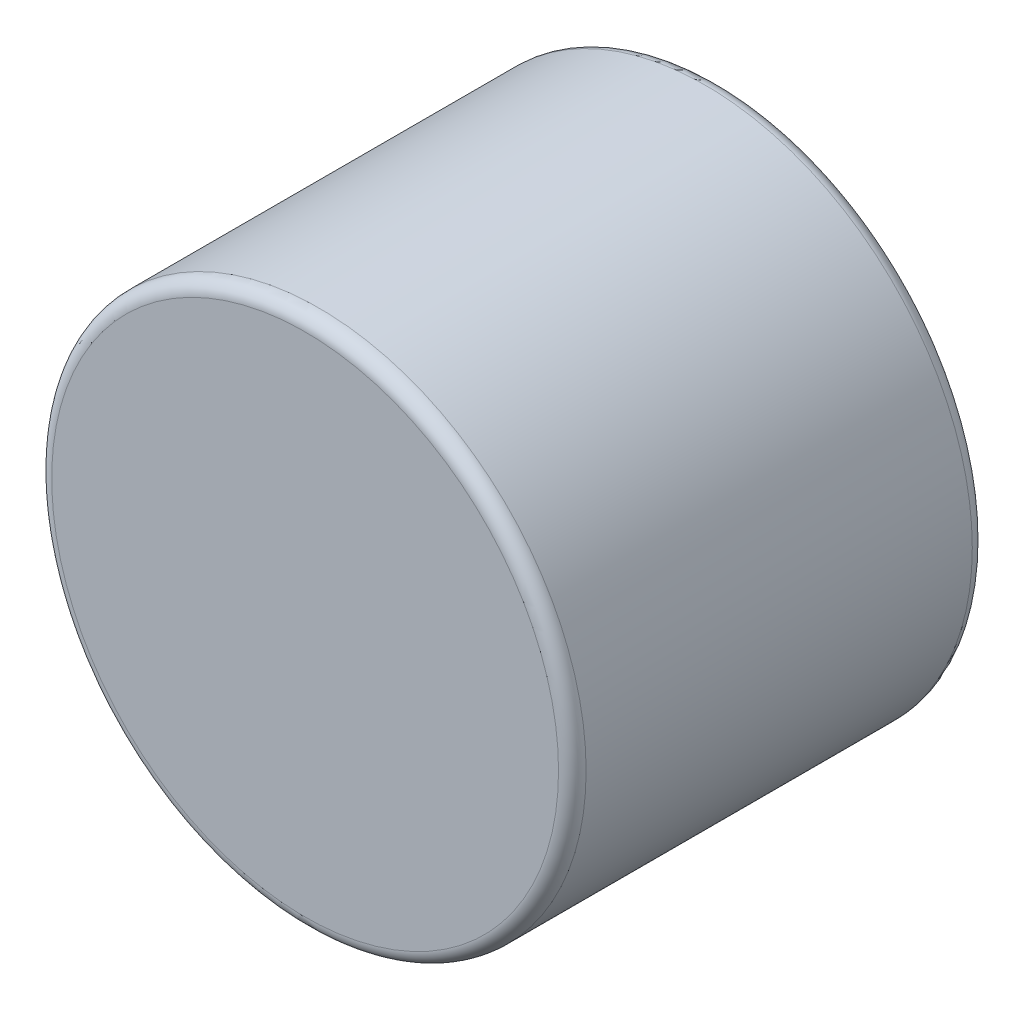
SolidWorks part; units mm, degrees
ref_plane "Front Plane" through (0, 0, 0) normal (0, 0, 1) x (1, 0, 0)
ref_plane "Top Plane" through (0, 0, 0) normal (0, 1, 0) x (1, 0, 0)
ref_plane "Right Plane" through (0, 0, 0) normal (1, 0, 0) x (0, 0, -1)
sketch "Sketch1" plane through (0, 0, 0) normal (0, 0, 1) x (1, 0, 0)
  circle A0 centre (0, 0) radius 49.2125
  dimension "D1" = 98.425
extrude "Boss-Extrude1" add sketch "Sketch1" along normal blind 76.2
fillet "Fillet1" radius 2.54 2 edges at (49.2125, 0, 0) (49.2125, 0, 76.2)
sketch "Sketch2" plane through (0, 0, 0) normal (0, 1, 0) x (1, 0, 0)
  line L0 (0, 0) -> (0, -73.66) construction
  line L1 (49.2125, -73.66) -> (-49.2125, -73.66) construction
